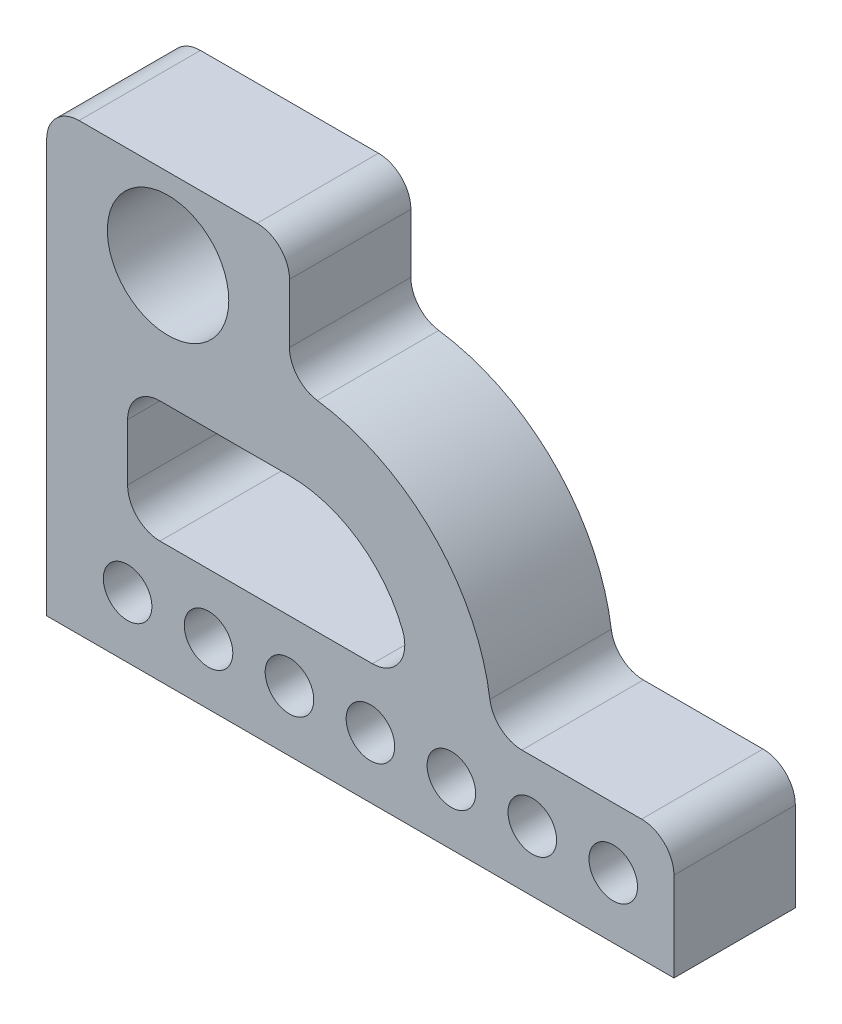
SolidWorks part; units mm, degrees
ref_plane "Front Plane" through (0, 0, 0) normal (0, 0, 1) x (1, 0, 0)
ref_plane "Top Plane" through (0, 0, 0) normal (0, 1, 0) x (1, 0, 0)
ref_plane "Right Plane" through (0, 0, 0) normal (1, 0, 0) x (0, 0, -1)
sketch "Sketch2" plane through (0, 0, 0) normal (0, 0, 1) x (1, 0, 0)
  line L0 (-90.8411, 71.558) -> (-90.8411, -30.442)
  line L1 (-90.8411, -30.442) -> (64.1589, -30.442)
  line L2 (64.1589, -30.442) -> (64.1589, -8.442)
  line L3 (-82.8411, 79.558) -> (-38.8411, 79.558)
  line L4 (-30.8411, 71.558) -> (-30.8411, 57.0036)
  line L5 (56.1589, -0.442) -> (26.6045, -0.442)
  line L6 (-62.8411, -0.442) -> (-10.3472, -0.442)
  line L7 (-30.8411, 29.558) -> (-62.8411, 29.558)
  line L8 (-70.8411, 21.558) -> (-70.8411, 7.558)
  arc A0 (-23.9446, 49.0801) -> (18.681, 6.4545) centre (-30.8411, -0.442) cw
  arc A1 (-2.8949, 10.4671) -> (-30.8411, 29.558) centre (-30.8411, -0.442) ccw
  circle A2 centre (-70.8411, -15.442) radius 6
  circle A3 centre (-50.8411, -15.442) radius 6
  circle A4 centre (-30.8411, -15.442) radius 6
  circle A5 centre (-10.8411, -15.442) radius 6
  circle A6 centre (9.1589, -15.442) radius 6
  circle A7 centre (29.1589, -15.442) radius 6
  circle A8 centre (49.1589, -15.442) radius 6
  arc A9 (64.1589, -8.442) -> (56.1589, -0.442) centre (56.1589, -8.442) ccw
  arc A10 (26.6045, -0.442) -> (18.681, 6.4545) centre (26.6045, 7.558) cw
  arc A11 (-23.9446, 49.0801) -> (-30.8411, 57.0036) centre (-22.8411, 57.0036) cw
  arc A12 (-30.8411, 71.558) -> (-38.8411, 79.558) centre (-38.8411, 71.558) ccw
  arc A13 (-90.8411, 71.558) -> (-82.8411, 79.558) centre (-82.8411, 71.558) cw
  arc A14 (-10.3472, -0.442) -> (-2.8949, 10.4671) centre (-10.3472, 7.558) ccw
  arc A15 (-62.8411, -0.442) -> (-70.8411, 7.558) centre (-62.8411, 7.558) cw
  arc A16 (-70.8411, 21.558) -> (-62.8411, 29.558) centre (-62.8411, 21.558) cw
  circle A17 centre (-60.8411, 59.558) radius 15
  point P29 (64.1589, -0.442)
  point P34 (-30.8411, 49.558)
  point P37 (-30.8411, 79.558)
  point P40 (-90.8411, 79.558)
  point P45 (-70.8411, -0.442)
  point P48 (-70.8411, 29.558)
  point P51 (0, 0)
  dimension "D6" = 50
  dimension "D7" = 20
  dimension "D8" = 30
  dimension "D10" = 12
  dimension "D12" = 15
  dimension "D13" = 8
  dimension "D14" = 8
  dimension "D15" = 30
  dimension "D16" = 20
  dimension "D1" = 60
  dimension "D2" = 30
  dimension "D3" = 110
  dimension "D4" = 155
  dimension "D5" = 30
  dimension "D9" = 30
  dimension "D11" = 7
extrude "Boss-Extrude1" add sketch "Sketch2" along normal blind 30 contours A17 | A16 L8 A15 L6 A14 A1 L7 | A3 | A4 | A6 | A7 | A8 | L0 L1 L2 A9 L5 A10 A0 A11 L4 A12 L3 A13 | A2 | A5
